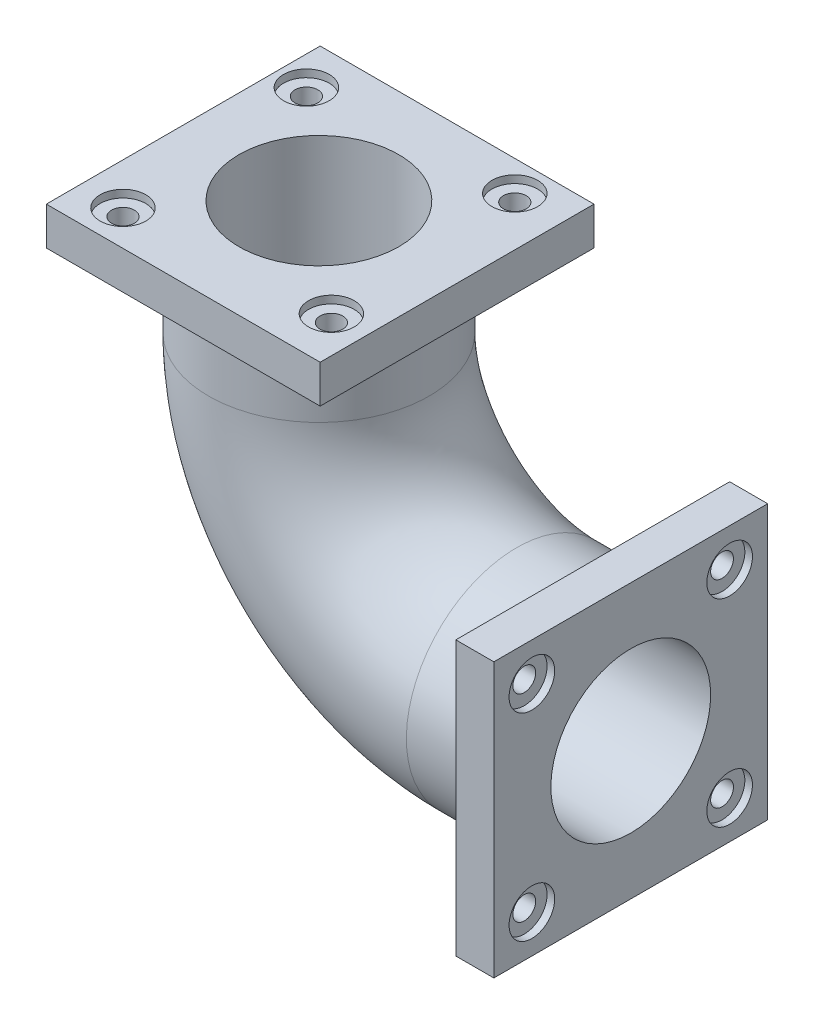
SolidWorks part; units mm, degrees
ref_plane "Front Plane" through (0, 0, 0) normal (0, 0, 1) x (1, 0, 0)
ref_plane "Top Plane" through (0, 0, 0) normal (0, 1, 0) x (1, 0, 0)
ref_plane "Right Plane" through (0, 0, 0) normal (1, 0, 0) x (0, 0, -1)
sketch "Sketch1" plane through (0, 0, 0) normal (0, 0, 1) x (1, 0, 0)
  line L0 (0, 0) -> (-150, 0)
  line L1 (-410, 260) -> (-410, 410)
  arc A0 (-150, 0) -> (-410, 260) centre (-150, 260) cw
  point P5 (0, 0)
  point P7 (0, 0)
  dimension "D2" = 260
  dimension "D1" = 150
sketch "Sketch2" plane through (0, 0, 0) normal (1, 0, 0) x (0, 0, -1)
  circle A0 centre (0, 0) radius 145
  dimension "D1" = 290
sweep "Sweep-Thin1" add profiles "Sketch2" path "Sketch1" parameters "D1"=40
sketch "Sketch3" plane through (0, 0, 0) normal (1, 0, 0) x (0, 0, -1)
  line L1 (180, -180) -> (-180, -180)
  line L2 (180, -180) -> (180, 180)
  line L3 (180, 180) -> (-180, 180)
  line L4 (-180, -180) -> (-180, 180)
  line L5 (180, -180) -> (-180, 180) construction
  line L6 (180, 180) -> (-180, -180) construction
  point P0 (0, 0)
  circle M4 centre (0, 0) radius 145
  dimension "D1" = 360
extrude "Boss-Extrude1" add sketch "Sketch3" against normal blind 50 contours L4 L1 L2 L3 M4
sketch "Sketch4" plane through (0, 410, 0) normal (0, 1, 0) x (1, 0, 0)
  line L1 (-225.2705, -183.0746) -> (-585.2705, -183.0746)
  line L2 (-225.2705, -183.0746) -> (-225.2705, 176.9254)
  line L3 (-225.2705, 176.9254) -> (-585.2705, 176.9254)
  line L4 (-585.2705, -183.0746) -> (-585.2705, 176.9254)
  line L5 (-225.2705, -183.0746) -> (-585.2705, 176.9254) construction
  line L6 (-225.2705, 176.9254) -> (-585.2705, -183.0746) construction
  point P0 (-405.2705, -3.0746)
  circle M4 centre (-410, 0) radius 145
  dimension "D1" = 360
extrude "Boss-Extrude2" add sketch "Sketch4" against normal blind 50 contours L4 L1 L2 L3 M4
sketch "Sketch5" plane through (0, 410, 0) normal (0, 1, 0) x (1, 0, 0)
  line L1 (-287.0014, -139.4439) -> (-547.0014, -139.4439) construction
  line L2 (-287.0014, -139.4439) -> (-287.0014, 120.5561) construction
  line L3 (-287.0014, 120.5561) -> (-547.0014, 120.5561) construction
  line L4 (-547.0014, -139.4439) -> (-547.0014, 120.5561) construction
  line L5 (-287.0014, -139.4439) -> (-547.0014, 120.5561) construction
  line L6 (-287.0014, 120.5561) -> (-547.0014, -139.4439) construction
  circle A0 centre (-547.0014, 120.5561) radius 30
  point P0 (-417.0014, -9.4439)
  dimension "D1" = 60
extrude "Cut-Extrude1" cut sketch "Sketch5" against normal blind 10
sketch "Sketch6" plane through (0, 400, 0) normal (0, 1, 0) x (1, 0, 0)
  circle A0 centre (-547.0014, 120.5561) radius 15
  dimension "D1" = 30
extrude "Cut-Extrude2" cut sketch "Sketch6" against normal blind 48
pattern_circular "CirPattern1" count 4 every 90 about axis through (-410, 0, 0) along (0, 1, 0) of "Cut-Extrude1", "Cut-Extrude2"
sketch "Sketch8" plane through (0, 0, 0) normal (1, 0, 0) x (0, 0, -1)
  line L1 (130, -130) -> (-130, -130) construction
  line L2 (130, -130) -> (130, 130) construction
  line L3 (130, 130) -> (-130, 130) construction
  line L4 (-130, -130) -> (-130, 130) construction
  line L5 (130, -130) -> (-130, 130) construction
  line L6 (130, 130) -> (-130, -130) construction
  circle A0 centre (-130, 130) radius 30
  point P0 (0, 0)
  dimension "D1" = 60
extrude "Cut-Extrude3" cut sketch "Sketch8" against normal blind 10
sketch "Sketch9" plane through (-10, 0, 0) normal (1, 0, 0) x (0, 0, -1)
  circle A0 centre (-130, 130) radius 15
  dimension "D1" = 30
extrude "Cut-Extrude4" cut sketch "Sketch9" against normal blind 49
pattern_circular "CirPattern2" count 4 every 90 about axis through (0, 0, 0) along (1, 0, 0) of "Cut-Extrude3", "Cut-Extrude4"
